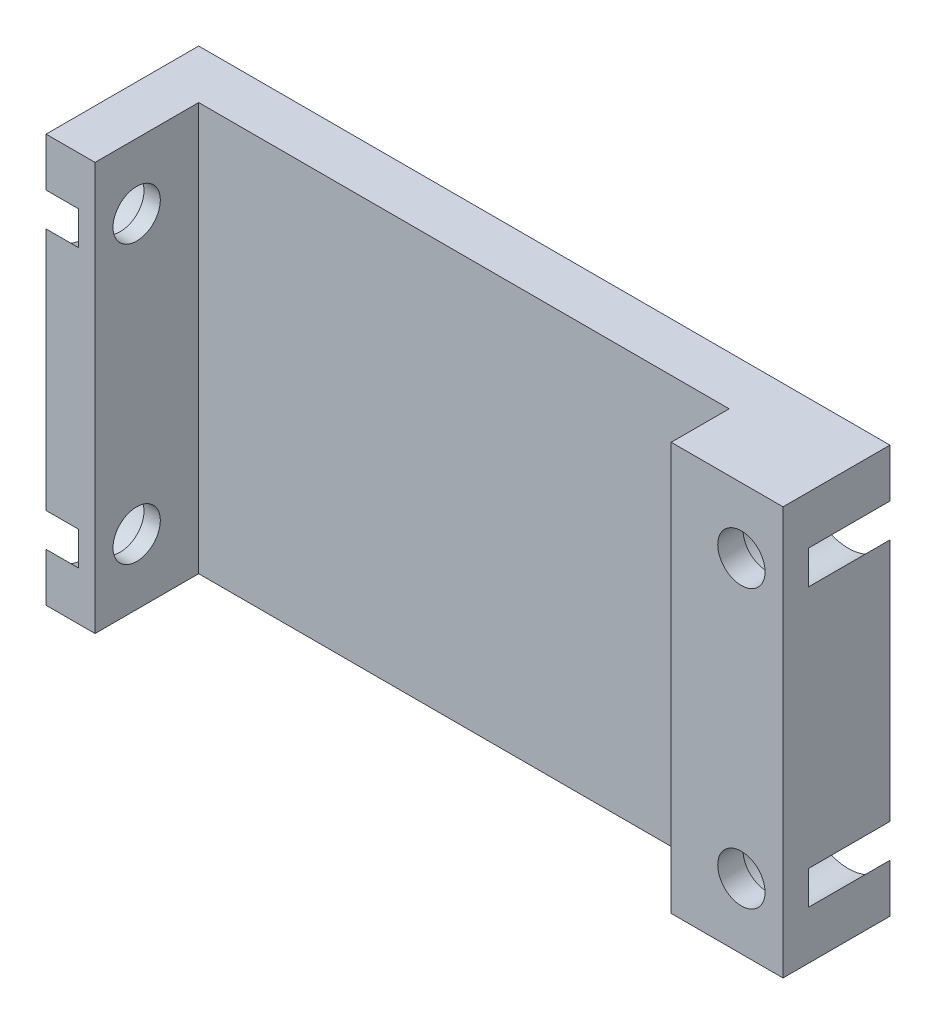
SolidWorks part; units mm, degrees
ref_plane "Plano frontal" through (0, 0, 0) normal (0, 0, 1) x (1, 0, 0)
ref_plane "Plano superior" through (0, 0, 0) normal (0, 1, 0) x (1, 0, 0)
ref_plane "Plano direito" through (0, 0, 0) normal (1, 0, 0) x (0, 0, -1)
other "Centro da massa"
sketch "Esboço2" plane through (0, 0, 0) normal (0, 0, 1) x (1, 0, 0)
  line L0 (0, 0) -> (0, -38.6) construction
  line L1 (-1.5, -22.5) -> (5.3501, -22.5)
  line L2 (-1.5, -22.5) -> (-1.5, 2.5)
  line L3 (-1.5, 2.5) -> (5.3501, 2.5)
  line L4 (5.3501, -22.5) -> (5.3501, 2.5)
  line L5 (2.8, -1.5) -> (2.8, 2.5) construction
  line L6 (2.8, -18.5) -> (2.8, -22.5) construction
  dimension "D1" = 0.25
  dimension "D2" = 4
  dimension "D3" = 1.5
extrude "Ressalto-extrusão2" add sketch "Esboço2" against normal offset from surface (3.55 mm away) 1 from offset 0.25 offset against normal yes
sketch "Esboço3" plane through (0, 0, -3.8) normal (0, 0, -1) x (-1, 0, 0)
  line L0 (33.75, 0) -> (33.75, -38.6) construction
  line L1 (-5.3501, 2.5) -> (34, 2.5)
  line L2 (-5.3501, 2.5) -> (-5.3501, -22.5)
  line L3 (-5.3501, -22.5) -> (34, -22.5)
  line L4 (34, 2.5) -> (34, -22.5)
  line L5 (-5.3501, -22.5) -> (1.5, -22.5) construction
  dimension "D1" = 0.25
extrude "Ressalto-extrusão3" add sketch "Esboço3" along normal blind 3
sketch "Esboço4" plane through (-34, 0, 0) normal (-1, 0, 0) x (0, 0, 1)
  line L1 (-6.8, -22.5) -> (2.55, -22.5)
  line L2 (-6.8, -22.5) -> (-6.8, 2.5)
  line L3 (-6.8, 2.5) -> (2.55, 2.5)
  line L4 (2.55, -22.5) -> (2.55, 2.5)
  line L5 (-6.8, 2.5) -> (-3.8, 2.5) construction
  dimension "D1" = 0.25
extrude "Ressalto-extrusão4" add sketch "Esboço4" along normal blind 3
hole_wizard "CBORE for M2.5 SHCS2" positions "3DSketch1" profile "Sketch1" counterbore size "M2.5" standard "ANSI Metric"
sketch3d "3DSketch1"
  circle A0 centre (-33.75, -1.5, 0) radius 1.35 construction
  circle A1 centre (-33.75, -18.5, 0) radius 1.35 construction
  point P0 (-37, -1.5, 0)
  point P7 (-32.4, -1.5, 0)
  point P8 (-37, -18.5, 0)
  point P20 (-32.4, -18.5, 0)
sketch "Sketch1" plane through (-37, -1.5, 0) normal (0, 1, 0) x (0, 0, 1)
  line L0 (0, 0) -> (0, 3.8712)
  line L1 (0, 3.8712) -> (1.45, 3)
  line L2 (1.45, 3) -> (1.45, 2)
  line L3 (1.45, 2) -> (2.75, 2)
  line L4 (2.75, 2) -> (2.75, 0)
  line L5 (2.75, 0) -> (0, 0)
  line L10 (0, 3.8712) -> (-1.45, 3) construction
  line L11 (0, -6.35) -> (0, 107.95) construction
  dimension "Hole Dia." = 2.9
  dimension "Hole Depth" = 3
  dimension "C'Bore Dia." = 5.5
  dimension "C'Bore Depth" = 2
  dimension "Drill Angle" = 118
hole_wizard "CBORE for M2.5 SHCS3" positions "Sketch2" profile "Sketch4" counterbore size "M2.5" standard "ANSI Metric" end condition up to next
sketch "Sketch2" plane through (0, 0, -6.8) normal (0, 0, -1) x (-1, 0, 0)
  circle A0 centre (-2.8, -1.5) radius 1.35 construction
  point P0 (-2.8, -1.5)
  point P6 (-2.8, -18.5)
sketch "Sketch4" plane through (2.8, -1.5, -6.8) normal (1, 0, 0) x (0, 1, 0)
  line L0 (0, 0) -> (0, 6.55)
  line L1 (0, 6.55) -> (1.45, 6.55)
  line L3 (1.45, 6.55) -> (1.45, 5)
  line L4 (1.45, 5) -> (2.75, 5)
  line L5 (2.75, 5) -> (2.75, 0)
  line L7 (2.75, 0) -> (0, 0)
  line L11 (0, -6.35) -> (0, 107.95) construction
  dimension "Thru Hole Dia." = 2.9
  dimension "Thru Hole Depth" = 6.55
  dimension "C'Bore Dia." = 5.5
  dimension "C'Bore Depth" = 5
move or copy body "Corpo-Mover/Copiar1" [suppressed] bodies to move or copy 104
